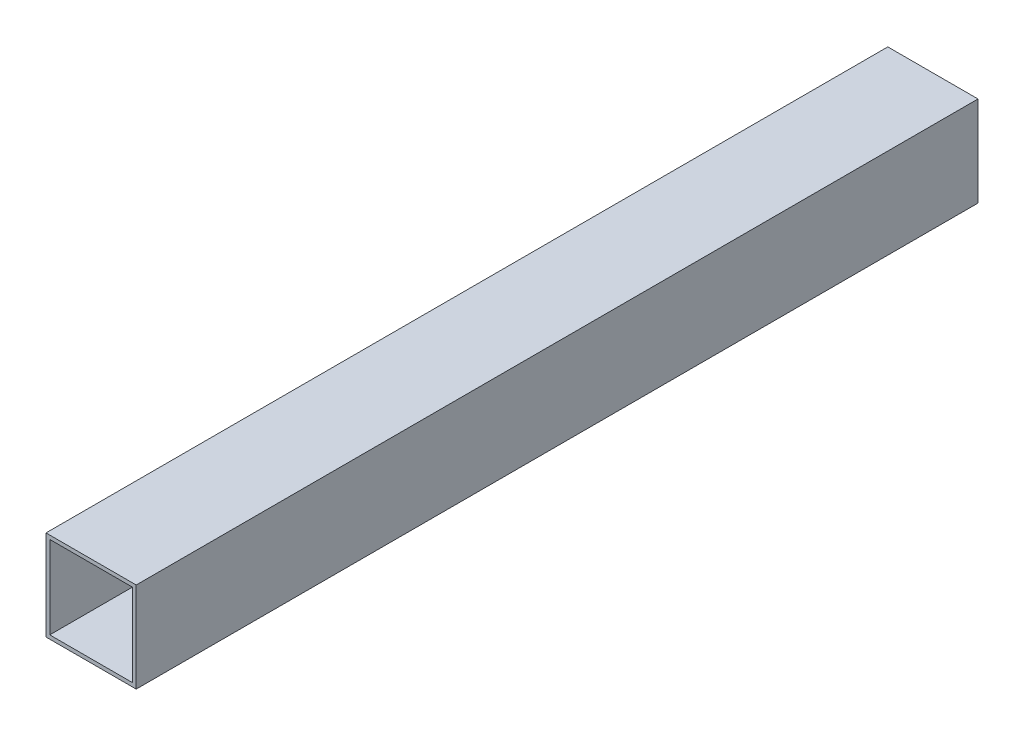
SolidWorks part; units mm, degrees
material "Custom Plastic"
ref_plane "Front Plane" through (0, 0, 0) normal (0, 0, 1) x (1, 0, 0)
ref_plane "Top Plane" through (0, 0, 0) normal (0, 1, 0) x (1, 0, 0)
ref_plane "Right Plane" through (0, 0, 0) normal (1, 0, 0) x (0, 0, -1)
sketch "Sketch2" plane through (0, 0, 0) normal (0, 0, 1) x (1, 0, 0)
  line L9 (-40.7297, 18.631) -> (35.4703, 18.631)
  line L10 (-40.7297, 18.631) -> (-40.7297, -57.569)
  line L11 (-40.7297, -57.569) -> (35.4703, -57.569)
  line L12 (35.4703, 18.631) -> (35.4703, -57.569)
extrude "Boss-Extrude1" add sketch "Sketch2" along normal blind 711.2 contours L10 L11 L12 L9
sketch "Sketch3" plane through (0, 0, 711.2) normal (0, 0, 1) x (1, 0, 0)
  line L0 (35.4703, 18.631) -> (35.4703, -57.569) construction
  line L1 (-40.7297, -57.569) -> (35.4703, -57.569) construction
  line L2 (-40.7297, 18.631) -> (-40.7297, -57.569) construction
  line L3 (-40.7297, 18.631) -> (35.4703, 18.631) construction
  line L4 (35.4703, 18.631) -> (35.4703, -57.569)
  line L5 (-40.7297, -57.569) -> (35.4703, -57.569)
  line L6 (-40.7297, 18.631) -> (-40.7297, -57.569)
  line L7 (-40.7297, 18.631) -> (35.4703, 18.631)
  line L9 (-37.5547, 15.456) -> (32.2953, 15.456)
  line L10 (-37.5547, 15.456) -> (-37.5547, -54.394)
  line L11 (-37.5547, -54.394) -> (32.2953, -54.394)
  line L12 (32.2953, 15.456) -> (32.2953, -54.394)
  dimension "D1" = 69.85
  dimension "D2" = 69.85
  dimension "D3" = 3.175
  dimension "D4" = 3.175
extrude "Cut-Extrude1" cut sketch "Sketch3" against normal blind 838.2 contours L10 L11 L12 L9
